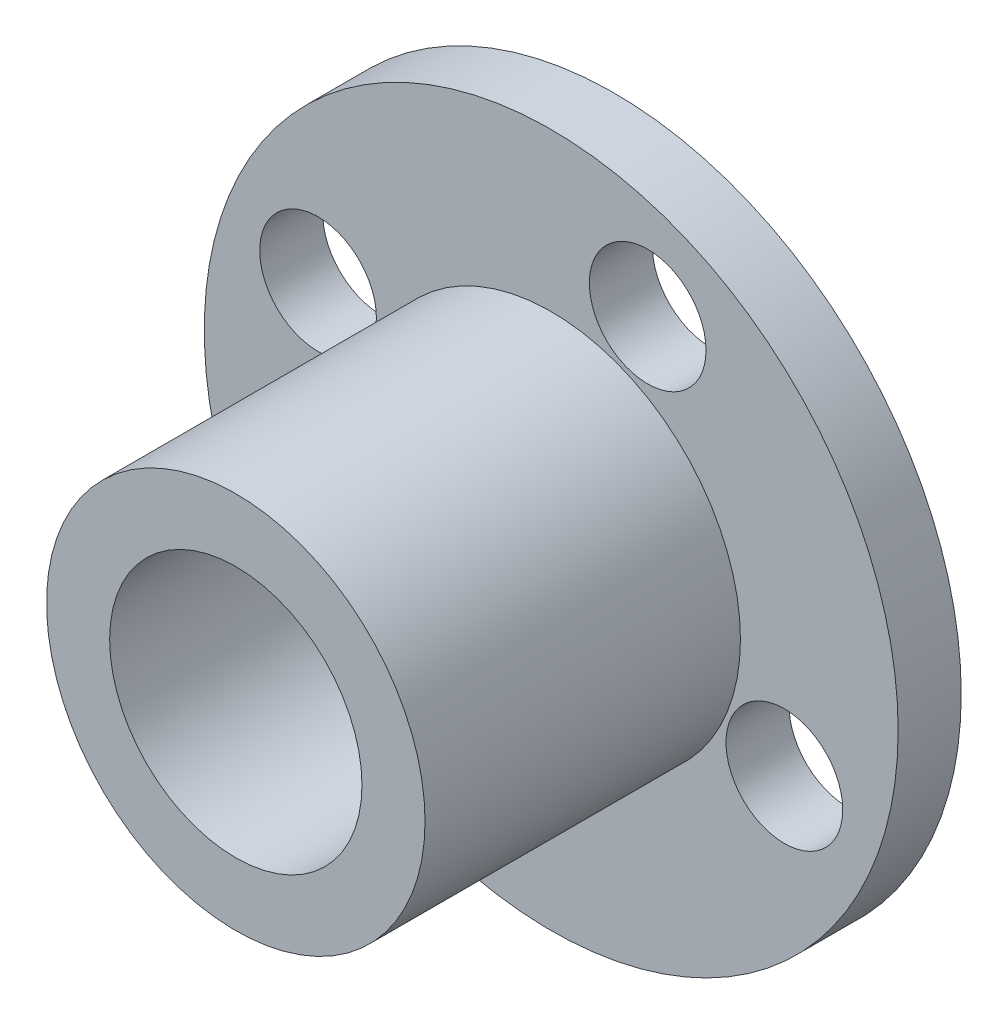
SolidWorks part; units mm, degrees
ref_plane "Front Plane" through (0, 0, 0) normal (1, 0, 0) x (0, 1, 0)
ref_plane "Top Plane" through (0, 0, 0) normal (0, 0, 1) x (0, 1, 0)
ref_plane "Right Plane" through (0, 0, 0) normal (0, 1, 0) x (-1, 0, 0)
sketch "Sketch1" plane through (0, 0, 0) normal (0, 0, 1) x (0, 1, 0)
  circle A0 centre (0, 0) radius 11
  circle A1 centre (-7.3922, 3.0585) radius 1.85
  circle A2 centre (3.0585, 7.3922) radius 1.85
  circle A3 centre (7.3922, -3.0585) radius 1.85
  circle A4 centre (-3.0585, -7.3922) radius 1.85
  dimension "D1" = 22
extrude "Boss-Extrude1" add sketch "Sketch1" along normal blind 2
sketch "Sketch2" plane through (0, 0, 2) normal (0, 0, 1) x (1, 0, 0)
  circle A0 centre (0, 0) radius 6
  dimension "D1" = 12
extrude "Boss-Extrude2" add sketch "Sketch2" along normal blind 10
sketch "Sketch4" plane through (0, 0, 0) normal (0, 0, -1) x (1, 0, 0)
  circle A0 centre (0, 0) radius 4
  dimension "D1" = 8
extrude "Cut-Extrude1" cut sketch "Sketch4" against normal blind 15
